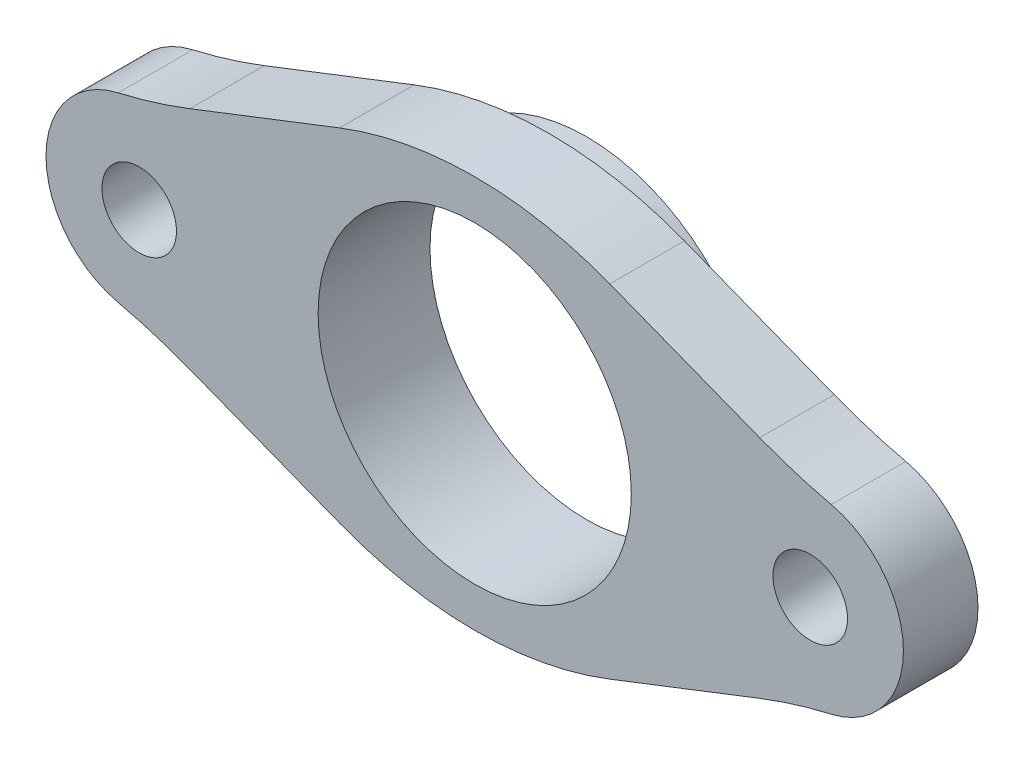
SolidWorks part; units mm, degrees
ref_plane "Front Plane" through (0, 0, 0) normal (0, 0, 1) x (1, 0, 0)
ref_plane "Top Plane" through (0, 0, 0) normal (0, 1, 0) x (1, 0, 0)
ref_plane "Right Plane" through (0, 0, 0) normal (1, 0, 0) x (0, 0, -1)
sketch "Sketch1" plane through (0, 0, 0) normal (0, 0, 1) x (1, 0, 0)
  line L5 (-54.3653, 227.8894) -> (-99.3659, 245.3894)
  line L6 (-99.3659, 245.3894) -> (-144.3653, 227.8894)
  line L7 (-54.3653, 202.8894) -> (-99.3659, 185.3894)
  line L8 (-99.3659, 185.3894) -> (-144.3653, 202.8894)
  circle A0 centre (-99.3659, 215.3894) radius 21
  circle A1 centre (-54.3653, 215.3894) radius 5
  circle A2 centre (-144.3653, 215.3894) radius 5
  arc A3 (-54.3653, 202.8894) -> (-54.3653, 227.8894) centre (-54.3653, 215.3894) ccw
  arc A4 (-144.3653, 227.8894) -> (-144.3653, 202.8894) centre (-144.3653, 215.3894) ccw
  dimension "D1" = 42
  dimension "D2" = 10
  dimension "D3" = 10
  dimension "D4" = 90
  dimension "D5" = 25
  dimension "D6" = 25
extrude "Boss-Extrude1" add sketch "Sketch1" along normal blind 10
fillet "Fillet1" radius 50 2 edges at (-99.3659, 185.3894, 5) (-99.3659, 245.3894, 5)
fillet "Fillet2" radius 70 4 edges at (-54.3653, 202.8894, 5) (-54.3653, 227.8894, 5) (-144.3653, 227.8894, 5) (-144.3653, 202.8894, 5)
sketch "Sketch2" plane through (0, 0, 10) normal (0, 0, 1) x (1, 0, 0)
  circle A0 centre (-99.3659, 215.3894) radius 23.5
  circle A1 centre (-99.3659, 215.3894) radius 21 construction
  circle A2 centre (-99.3659, 215.3894) radius 21
  dimension "D1" = 47
extrude "Boss-Extrude2" add sketch "Sketch2" against normal blind 15
